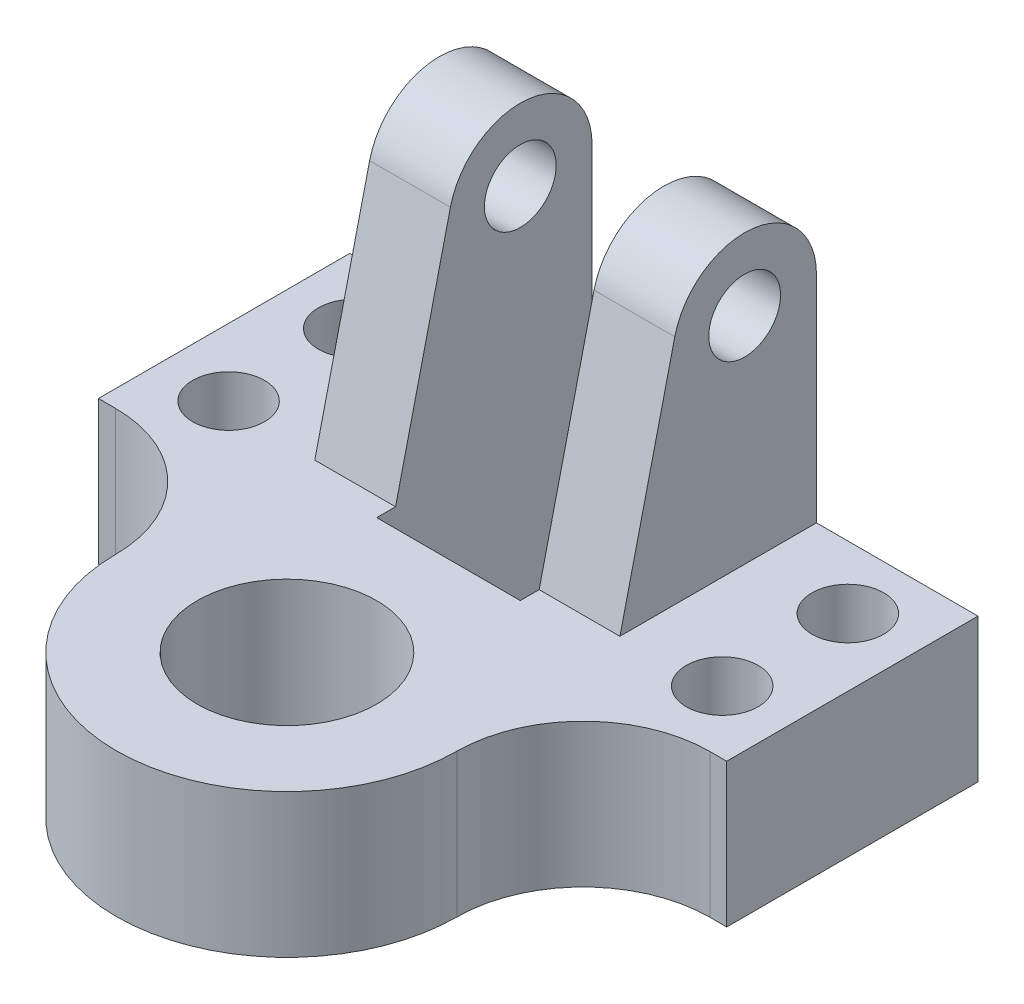
SolidWorks part; units mm, degrees
ref_plane "前视基准面" through (0, 0, 0) normal (0, 0, 1) x (1, 0, 0)
ref_plane "上视基准面" through (0, 0, 0) normal (0, 1, 0) x (1, 0, 0)
ref_plane "右视基准面" through (0, 0, 0) normal (1, 0, 0) x (0, 0, -1)
other "Configuration Table"
sketch "草图1" plane through (0, 0, 0) normal (0, 1, 0) x (1, 0, 0)
  line L0 (-1391.0776, -1422.4) -> (-578.2776, -1422.4)
  line L1 (2164.9224, -1422.4) -> (2164.9224, 0)
  line L2 (2164.9224, 0) -> (793.3224, 0)
  line L3 (-1391.0776, -1422.4) -> (-1391.0776, 0)
  line L4 (-1391.0776, 0) -> (-19.4776, 0)
  line L5 (-19.4776, 0) -> (-19.4776, -1219.2)
  line L8 (793.3224, 0) -> (793.3224, -1219.2)
  line L9 (793.3224, -1219.2) -> (-19.4776, -1219.2)
  line L10 (-578.2776, -1422.4) -> (-578.2776, -2133.6)
  line L11 (-578.2776, -2133.6) -> (-578.2776, -2137.6522)
  line L12 (1352.1224, -1422.4) -> (1352.1224, -2133.6)
  line L13 (1352.1224, -1422.4) -> (2164.9224, -1422.4)
  line L15 (-1010.0776, -355.6) -> (1783.9224, -355.6) construction
  line L16 (-1010.0776, -355.6) -> (-1010.0776, -1066.8) construction
  line L17 (-1010.0776, -1066.8) -> (1783.9224, -1066.8) construction
  line L18 (1783.9224, -355.6) -> (1783.9224, -1066.8) construction
  arc A0 (-578.2776, -2133.6) -> (1352.1224, -2133.6) centre (386.9224, -2133.6) ccw
  circle A1 centre (-1010.0776, -355.6) radius 203.2
  circle A2 centre (-1010.0776, -1066.8) radius 203.2
  circle A3 centre (1783.9224, -355.6) radius 203.2
  circle A4 centre (1783.9224, -1066.8) radius 203.2
  circle A5 centre (386.9224, -2133.6) radius 508
  dimension "D2" = 1422.4
extrude "凸台-拉伸1" add sketch "草图1" along normal blind 812.8 contours L10 A0 L12 L13 L1 L2 L8 L9 L5 L4 L3 L0 A5 A4 A3 A2 A1
fillet "圆角3" radius 717.55 2 edges at (1352.1224, 406.4, 1422.4) (-578.2776, 406.4, 1422.4)
sketch "草图5" plane through (793.3224, 0, 0) normal (-1, 0, 0) x (0, 0, 1)
  line L0 (0, 812.8) -> (0, 2032)
  line L1 (0, 812.8) -> (1112.386, 812.8)
  line L3 (1422.4, 812.8) -> (0, 812.8) construction
  line L4 (1112.386, 812.8) -> (801.8878, 2125.5432)
  arc A0 (801.8878, 2125.5432) -> (0, 2032) centre (406.4, 2032) ccw
  circle A1 centre (406.4, 2032) radius 203.2
extrude "凸台-拉伸4" add sketch "草图5" against normal blind 457.2
ref_plane "基准面1" through (386.9224, 0, 0) normal (-1, 0, 0) x (0, 0, 1)
mirror "镜向1" about plane through (386.9224, 0, 0) normal (-1, 0, 0) of "凸台-拉伸4"
